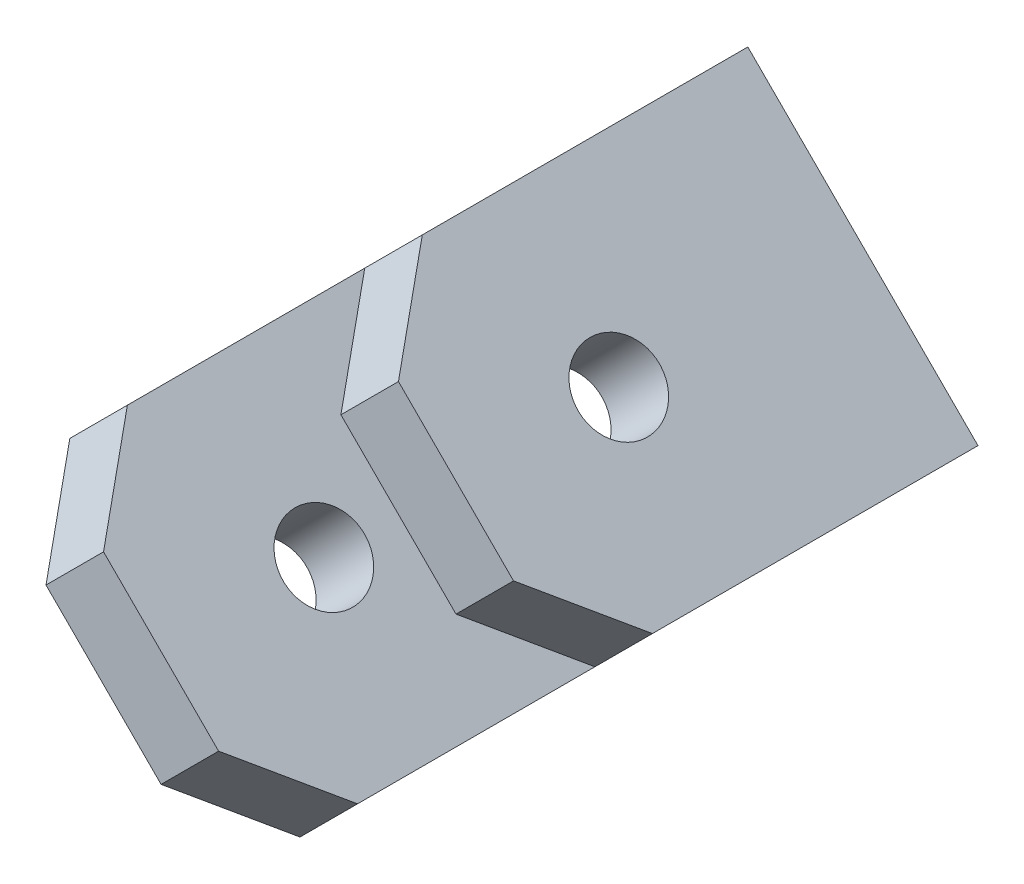
SolidWorks part; units mm, degrees
ref_plane "Front" through (0, 0, 0) normal (0, 0, 1) x (1, 0, 0)
ref_plane "Top" through (0, 0, 0) normal (0, 1, 0) x (1, 0, 0)
ref_plane "Right" through (0, 0, 0) normal (1, 0, 0) x (0, 0, -1)
sketch "Sketch1" plane through (0, 0, 0) normal (0, 0, 1) x (1, 0, 0)
  line L0 (-72.9646, -1.1225) -> (-1.1225, -72.9646)
  line L1 (-72.9646, -1.1225) -> (1.1225, 72.9646) construction
  line L2 (-1.1225, -72.9646) -> (72.9646, 1.1225) construction
  line L3 (1.1225, 72.9646) -> (72.9646, 1.1225)
  line L4 (37.0436, 37.0436) -> (-37.0436, -37.0436) construction
  line L5 (0, 0) -> (38.396, 0) construction
  line L6 (1.1225, 72.9646) -> (19.083, 90.9251)
  line L7 (19.083, 90.9251) -> (90.9251, 19.083)
  line L8 (90.9251, 19.083) -> (72.9646, 1.1225)
  line L9 (-72.9646, -1.1225) -> (-90.9251, -19.083)
  line L10 (-90.9251, -19.083) -> (-19.083, -90.9251)
  line L11 (-19.083, -90.9251) -> (-1.1225, -72.9646)
  dimension "D1" = 45
  dimension "D2" = 104.775
  dimension "D3" = 25.4
  dimension "D4" = 101.6
extrude "Extrude1" add sketch "Sketch1" along normal blind 127
sketch "Sketch3" plane through (55.0041, 55.0041, 0) normal (0.7071, 0.7071, 0) x (0, 0, -1)
  line L0 (-127, -25.4) -> (-101.6, -50.8)
  line L1 (-127, -50.8) -> (-127, 50.8) construction
  line L2 (-127, -50.8) -> (0, -50.8) construction
  line L3 (-127, 25.4) -> (-101.6, 50.8)
  line L4 (-127, 50.8) -> (0, 50.8) construction
  line L5 (-127, 0) -> (-76.2, 0) construction
  line L6 (-101.6, -50.8) -> (-127, -50.8)
  line L7 (-127, -50.8) -> (-127, -25.4)
  line L8 (-127, 25.4) -> (-127, 50.8)
  line L9 (-127, 50.8) -> (-101.6, 50.8)
  circle A0 centre (-76.2, 0) radius 12.7
  dimension "D1" = 25.4
  dimension "D2" = 50.8
  dimension "D3" = 50.8
extrude "Cut-Extrude1" cut sketch "Sketch3" against normal through all
